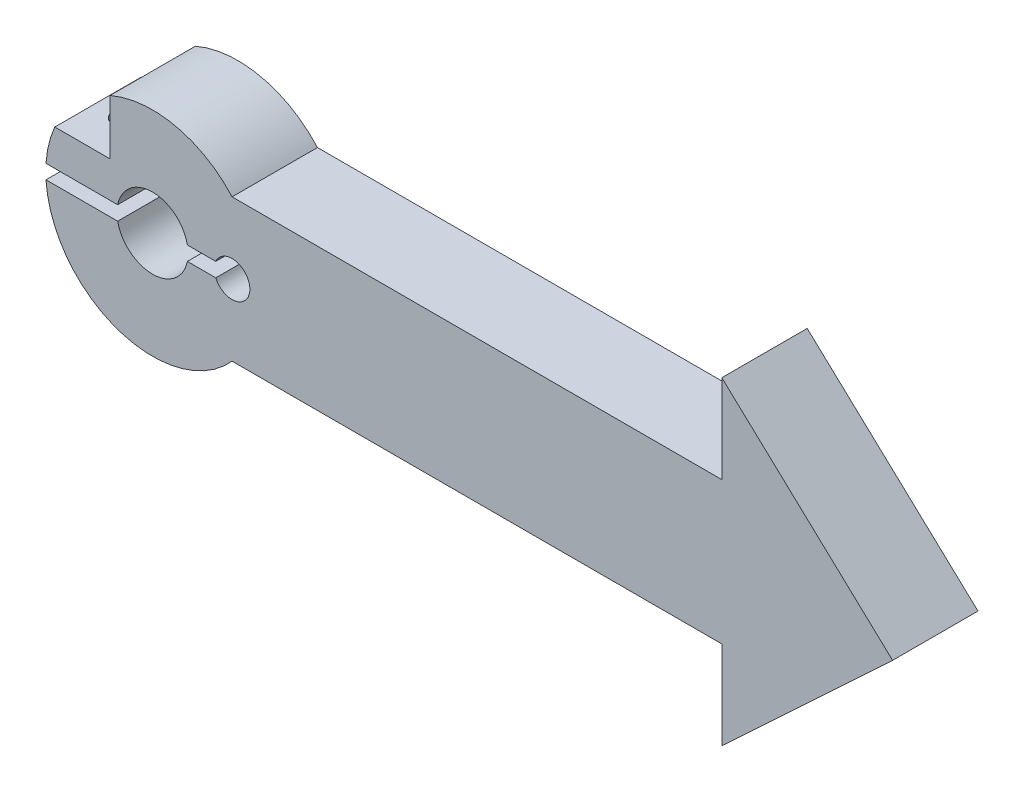
SolidWorks part; units mm, degrees
material "ABS"
ref_plane "Front Plane" through (0, 0, 0) normal (0, 0, 1) x (1, 0, 0)
ref_plane "Top Plane" through (0, 0, 0) normal (0, 1, 0) x (1, 0, 0)
ref_plane "Right Plane" through (0, 0, 0) normal (1, 0, 0) x (0, 0, -1)
sketch "Sketch1" plane through (0, 0, 0) normal (0, 0, 1) x (1, 0, 0)
  line L0 (0, 0) -> (101.6, 0) construction
  line L1 (14.199, -12.7) -> (101.6, -12.7)
  line L2 (14.199, 12.7) -> (101.6, 12.7)
  line L3 (0, 12.7) -> (101.6, 12.7) construction
  line L4 (0, -12.7) -> (101.6, -12.7) construction
  line L5 (101.6, 0) -> (132.08, 0) construction
  line L6 (101.6, 12.7) -> (101.6, 28.448)
  line L7 (101.6, 28.448) -> (132.08, 0)
  line L8 (101.6, -12.7) -> (101.6, -28.448)
  line L9 (101.6, -28.448) -> (132.08, 0)
  line L10 (14.199, 0) -> (-23.4907, 0) construction
  line L11 (11.2891, 1.27) -> (6.2217, 1.27)
  line L12 (11.2891, -1.27) -> (6.2217, -1.27)
  line L13 (14.199, 1.27) -> (-23.4907, 1.27) construction
  line L14 (14.199, -1.27) -> (-23.4907, -1.27) construction
  line L15 (-6.2217, -1.27) -> (-19.0076, -1.27)
  line L16 (-19.0076, 1.27) -> (-6.2217, 1.27)
  arc A0 (-6.2217, -1.27) -> (6.2217, -1.27) centre (0, 0) ccw
  arc A1 (14.199, 12.7) -> (-19.0076, 1.27) centre (0, 0) ccw
  arc A2 (11.2891, -1.27) -> (11.2891, 1.27) centre (14.199, 0) ccw
  arc A3 (-19.0076, -1.27) -> (14.199, -12.7) centre (0, 0) ccw
  arc A4 (6.2217, 1.27) -> (-6.2217, 1.27) centre (0, 0) ccw
  dimension "D1" = 12.7
  dimension "D5" = 19.05
  dimension "D9" = 6.35
  dimension "D2" = 101.6
  dimension "D6" = 132.08
  dimension "D7" = 15.748
  dimension "D8" = 15.748
  dimension "D12" = 14.199
  dimension "D3" = 12.7
  dimension "D4" = 12.7
  dimension "D10" = 1.27
  dimension "D11" = 1.27
extrude "Boss-Extrude1" add sketch "Sketch1" along normal blind 15.24
sketch "Sketch2" plane through (0, 0, 0) normal (0, 1, 0) x (1, 0, 0)
  line L0 (-19.0076, -7.62) -> (-6.2217, -7.62) construction
  line L1 (-19.0076, -15.24) -> (-19.0076, 0) construction
  line L2 (-6.2217, -15.24) -> (-6.2217, 0) construction
  circle A0 centre (-12.6147, -7.62) radius 2.032
  dimension "D1" = 4.064
extrude "Cut-Extrude1" cut sketch "Sketch2" against normal through all and the other way through all
sketch "Sketch3" plane through (0, 0, 15.24) normal (0, 0, 1) x (1, 0, 0)
  line L1 (-7.5864, 7.6788) -> (-21.5478, 7.6788)
  line L2 (-7.5864, 7.6788) -> (-7.5864, 22.6374)
  line L3 (-7.5864, 22.6374) -> (-21.5478, 22.6374)
  line L4 (-21.5478, 7.6788) -> (-21.5478, 22.6374)
  dimension "D1" = 7.5864
  dimension "D2" = 13.9614
  dimension "D3" = 14.9586
  dimension "D4" = 7.6788
extrude "Cut-Extrude2" cut sketch "Sketch3" against normal through all
